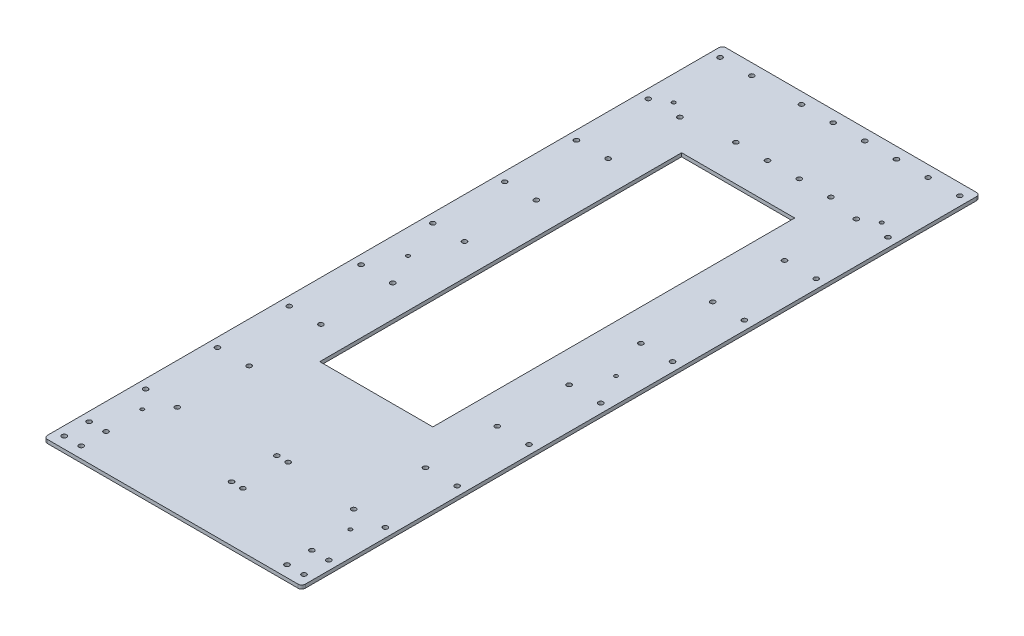
SolidWorks part; units mm, degrees
ref_plane "Front Plane" through (0, 0, 0) normal (0, 0, 1) x (1, 0, 0)
ref_plane "Top Plane" through (0, 0, 0) normal (0, 1, 0) x (1, 0, 0)
ref_plane "Right Plane" through (0, 0, 0) normal (1, 0, 0) x (0, 0, -1)
sketch "Sketch1" plane through (0, 0, 0) normal (0, 1, 0) x (1, 0, 0)
  line L0 (92, 300) -> (92, -300) construction
  line L1 (-114, -300) -> (114, -300)
  line L2 (-114, -300) -> (-114, 300)
  line L3 (-114, 300) -> (114, 300)
  line L4 (114, -300) -> (114, 300)
  line L5 (-114, -300) -> (114, 300) construction
  line L6 (-114, 300) -> (114, -300) construction
  line L7 (-114, 0) -> (114, 0) construction
  line L8 (0, 300) -> (0, -300) construction
  line L9 (78, 290) -> (50, 290) construction
  line L10 (72.9634, -279) -> (112.2482, -279) construction
  line L11 (-50, -120) -> (50, -120)
  line L12 (-50, -120) -> (-50, 200)
  line L13 (-50, 200) -> (50, 200)
  line L14 (50, -120) -> (50, 200)
  line L15 (-24, -231) -> (28.6506, -231) construction
  circle A0 centre (106, 290) radius 2.1
  circle A10 centre (106, -290) radius 2.1
  circle A11 centre (78, -290) radius 2.1 construction
  circle A21 centre (78, 290) radius 2.1
  circle A22 centre (92, 0) radius 1.6
  circle A23 centre (92, 235) radius 1.6
  circle A24 centre (92, -235) radius 1.6
  circle A34 centre (-92, -235) radius 1.6
  circle A42 centre (-78, -290) radius 2.1 construction
  circle A43 centre (-106, -290) radius 2.1
  circle A50 centre (50, 290) radius 2.1
  circle A51 centre (22, 290) radius 2.1
  circle A52 centre (-6, 290) radius 2.1
  circle A53 centre (-34, 290) radius 2.1
  circle A55 centre (50, 232) radius 2.1
  circle A56 centre (22, 232) radius 2.1
  circle A57 centre (-6, 232) radius 2.1
  circle A58 centre (-34, 232) radius 2.1
  circle A61 centre (78, 232) radius 2.1 [skipped]
  circle A62 centre (91, -290) radius 2.1
  circle A63 centre (91, -268) radius 2.1
  circle A64 centre (106, -268) radius 2.1
  circle A65 centre (-91, -290) radius 2.1
  circle A66 centre (-106, -268) radius 2.1
  circle A67 centre (-91, -268) radius 2.1
  circle A68 centre (13, -251) radius 2.1
  circle A69 centre (3, -251) radius 2.1
  circle A70 centre (13, -211) radius 2.1
  circle A71 centre (3, -211) radius 2.1
  circle A72 centre (-62, 232) radius 2.1 [skipped]
  circle A73 centre (-62, 290) radius 2.1 [skipped]
  circle A74 centre (106, -232) radius 2.1 [skipped]
  circle A75 centre (106, -174) radius 2.1 [skipped]
  circle A76 centre (106, -116) radius 2.1 [skipped]
  circle A77 centre (106, -58) radius 2.1 [skipped]
  circle A78 centre (106, 0) radius 2.1 [skipped]
  circle A79 centre (106, 58) radius 2.1 [skipped]
  circle A80 centre (106, 116) radius 2.1 [skipped]
  circle A81 centre (106, 174) radius 2.1 [skipped]
  circle A82 centre (106, 232) radius 2.1 [skipped]
  circle A83 centre (106, 226.5) radius 2.1
  circle A84 centre (106, 163) radius 2.1
  circle A85 centre (106, 99.5) radius 2.1
  circle A86 centre (106, 36) radius 2.1
  circle A87 centre (106, -27.5) radius 2.1
  circle A88 centre (106, -91) radius 2.1
  circle A89 centre (106, -154.5) radius 2.1
  circle A90 centre (106, -218) radius 2.1
  circle A91 centre (78, 226.5) radius 2.1
  circle A92 centre (78, 163) radius 2.1
  circle A93 centre (78, 99.5) radius 2.1
  circle A94 centre (78, 36) radius 2.1
  circle A95 centre (78, -27.5) radius 2.1
  circle A96 centre (78, -91) radius 2.1
  circle A97 centre (78, -154.5) radius 2.1
  circle A98 centre (78, -218) radius 2.1
  circle A99 centre (-78, -218) radius 2.1
  circle A100 centre (-78, -154.5) radius 2.1
  circle A101 centre (-106, -218) radius 2.1
  circle A102 centre (-106, -154.5) radius 2.1
  circle A103 centre (-78, -91) radius 2.1
  circle A104 centre (-78, -27.5) radius 2.1
  circle A105 centre (-106, -91) radius 2.1
  circle A106 centre (-106, -27.5) radius 2.1
  circle A107 centre (-78, 36) radius 2.1
  circle A108 centre (-78, 99.5) radius 2.1
  circle A109 centre (-106, 36) radius 2.1
  circle A110 centre (-106, 99.5) radius 2.1
  circle A111 centre (-78, 163) radius 2.1
  circle A112 centre (-106, 163) radius 2.1
  circle A113 centre (-78, 226.5) radius 2.1
  circle A114 centre (-106, 226.5) radius 2.1
  circle A115 centre (-92, 235) radius 1.6
  circle A116 centre (-106, 290) radius 2.1
  circle A117 centre (-78, 290) radius 2.1
  circle A118 centre (-92, 0) radius 1.6
  point P0 (0, 0)
  point P112 (0, 0)
  dimension "D5" = 4.2
  dimension "D8" = 3.2
  dimension "D9" = 3.2
  dimension "D19" = 4.2
  dimension "D23" = 4.2
  dimension "D25" = 4.2
  dimension "D1" = 600
  dimension "D2" = 228
  dimension "D3" = 22
  dimension "D4" = 14
  dimension "D6" = 10
  dimension "D10" = 235
  dimension "D13" = 28
  dimension "D14" = 58
  dimension "D15" = 100
  dimension "D16" = 200
  dimension "D17" = 120
  dimension "D18" = 50
  dimension "D20" = 15
  dimension "D21" = 11
  dimension "D24" = 20
  dimension "D26" = 10
  dimension "D27" = 127
  dimension "D22" = 69
  dimension "D28" = 21
  dimension "D7" = 11
  dimension "D11" = 6
  dimension "D12" = 2
  dimension "D29" = 9
extrude "Boss-Extrude1" add sketch "Sketch1" along normal blind 3.175
fillet "Fillet1" radius 3.2 4 edges at (114, 1.5875, 300) (-114, 1.5875, 300) (-114, 1.5875, -300) (114, 1.5875, -300)
equation "\"m4\"= 4.2"
equation "\"m3\"=3.2"
equation "\"D5@Sketch1\"=\"m4\""
equation "\"width\"=228"
equation "\"height\"= 600"
equation "\"D2@Sketch1\"=\"width\""
equation "\"D1@Sketch1\"=\"height\""
equation "\"D8@Sketch1\"=\"m3\""
equation "\"D9@Sketch1\"=\"m3\""
equation "\"D19@Sketch1\"=\"m4\""
equation "\"D23@Sketch1\"=\"m4\""
equation "\"D25@Sketch1\"=\"m4\"'"
